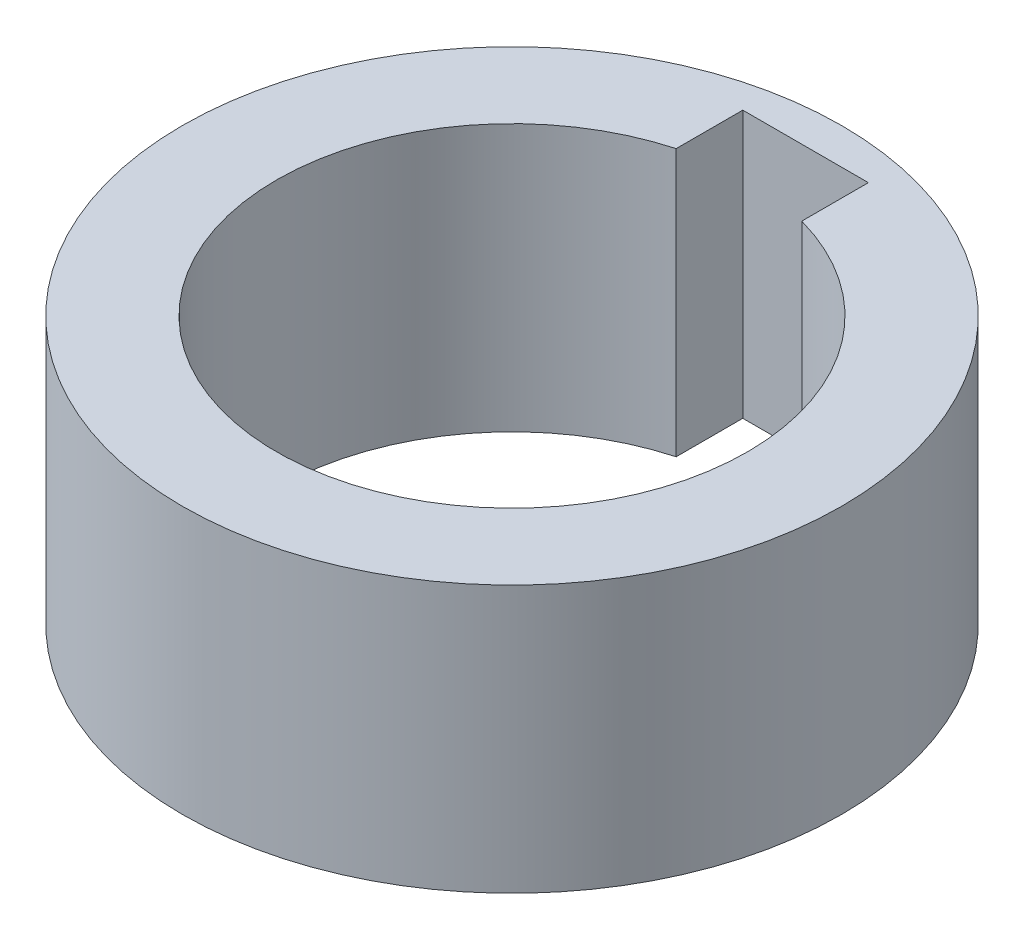
SolidWorks part; units mm, degrees
ref_plane "Front Plane" through (0, 0, 0) normal (0, 0, 1) x (1, 0, 0)
ref_plane "Top Plane" through (0, 0, 0) normal (0, 1, 0) x (1, 0, 0)
ref_plane "Right Plane" through (0, 0, 0) normal (1, 0, 0) x (0, 0, -1)
sketch "Sketch1" plane through (0, 0, 0) normal (0, 1, 0) x (1, 0, 0)
  circle A0 centre (0, 0) radius 15
  circle A1 centre (0, 0) radius 21
extrude "Boss-Extrude1" add sketch "Sketch1" against normal blind 17
sketch "Sketch2" plane through (0, 0, 0) normal (0, 1, 0) x (1, 0, 0)
  line L0 (0, 15) -> (0, 18.7) construction
  line L1 (4, 18.7) -> (-4, 18.7)
  line L2 (-4, 18.7) -> (-4, 14.4568)
  line L3 (4, 18.7) -> (4, 14.4568)
  circle A0 centre (0, 0) radius 15 construction
  arc A1 (4, 14.4568) -> (-4, 14.4568) centre (0, 0) ccw
extrude "Cut-Extrude1" cut sketch "Sketch2" against normal through all contours A1 L2 L1 L3
